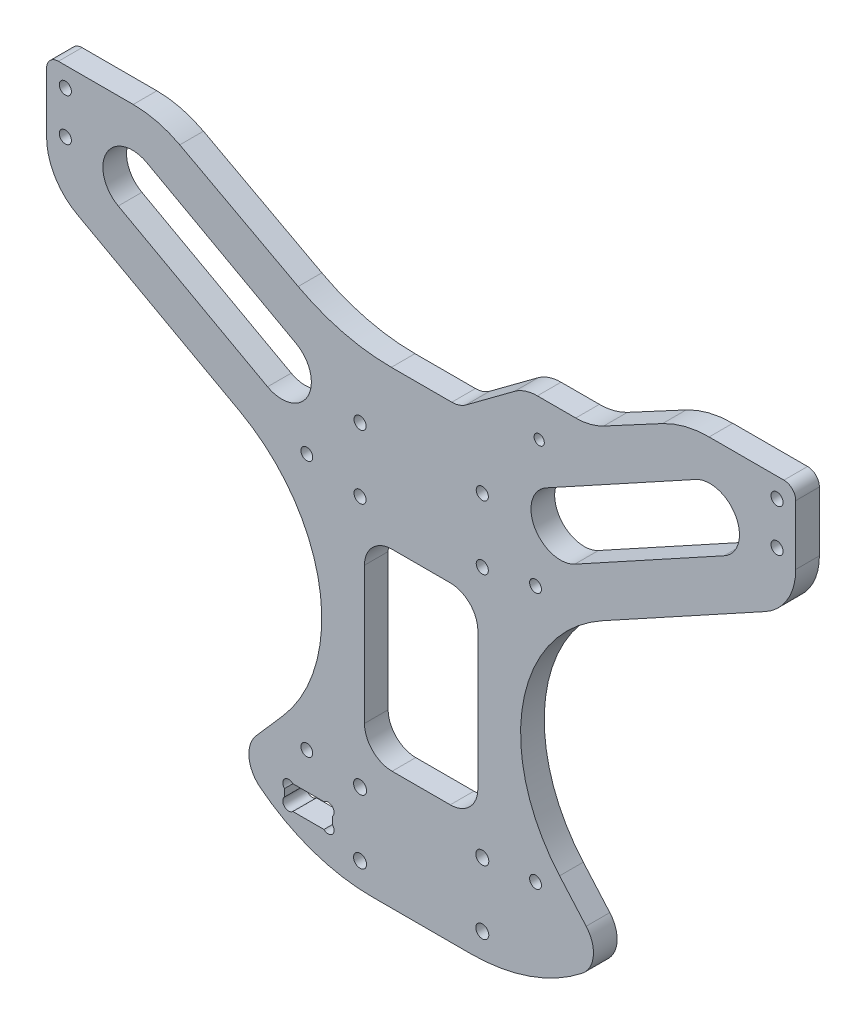
SolidWorks part; units mm, degrees
ref_plane "Front Plane" through (0, 0, 0) normal (0, 0, 1) x (1, 0, 0)
ref_plane "Top Plane" through (0, 0, 0) normal (0, 1, 0) x (1, 0, 0)
ref_plane "Right Plane" through (0, 0, 0) normal (1, 0, 0) x (0, 0, -1)
ref_plane "Plane1" through (0, 0, 0) normal (0, 0, -1) x (-1, 0, 0)
sketch "Sketch1" plane through (0, 0, 0) normal (0, 0, -1) x (-1, 0, 0)
  line L0 (190, 233.5) -> (190, 287.5)
  line L1 (190, 287.5) -> (-190, 287.5)
  line L2 (-190, 287.5) -> (-190, 233.5)
  line L3 (-190, 233.5) -> (-91.9961, 179.7332)
  line L4 (-70.2149, 56.792) -> (-93.1615, 30.5402)
  line L5 (-25, 0) -> (25, 0)
  line L6 (93.1615, 30.5402) -> (70.2149, 56.792)
  line L7 (91.9961, 179.7332) -> (190, 233.5)
  arc A0 (-91.9961, 179.7332) -> (-70.2149, 56.792) centre (-130.5233, 109.5074) cw
  arc A1 (-93.1615, 30.5402) -> (-25, 0) centre (-25, 91.3336) ccw
  arc A2 (25, 0) -> (93.1615, 30.5402) centre (25, 91.3336) ccw
  arc A3 (70.2149, 56.792) -> (91.9961, 179.7332) centre (130.5233, 109.5074) cw
  circle A4 centre (-59.8577, 243.186) radius 2.6
extrude "Boss-Extrude1" add sketch "Sketch1" against normal blind 12
sketch "Sketch2" plane through (0, 0, 12) normal (0, 0, 1) x (1, 0, 0)
  line L0 (133.5, 287.5) -> (-133.5, 287.5)
  line L1 (-133.5, 287.5) -> (-40.2504, 237.5)
  line L2 (-40.2504, 237.5) -> (19.5, 237.5)
  line L3 (19.5, 237.5) -> (52.5, 262)
  line L4 (52.5, 262) -> (85.9427, 262)
  line L5 (85.9427, 262) -> (133.5, 287.5)
extrude "Cut-Extrude1" cut sketch "Sketch2" against normal through all
sketch "Sketch3" plane through (0, 0, 0) normal (0, 0, -1) x (-1, 0, 0)
  line L0 (28.75, 60.25) -> (28.75, 157.75)
  line L1 (28.75, 157.75) -> (-28.75, 157.75)
  line L2 (-28.75, 157.75) -> (-28.75, 60.25)
  line L3 (-28.75, 60.25) -> (28.75, 60.25)
extrude "Cut-Extrude2" cut sketch "Sketch3" against normal through all
sketch "Sketch4" plane through (0, 0, 0) normal (0, 0, -1) x (-1, 0, 0)
  line L0 (-153.664, 239.1065) -> (-77.9148, 197.5491)
  line L1 (-63.4852, 223.8509) -> (-139.2344, 265.4083)
  arc A0 (-77.9148, 197.5491) -> (-63.4852, 223.8509) centre (-70.7, 210.7) ccw
  arc A1 (-139.2344, 265.4083) -> (-153.664, 239.1065) centre (-146.4492, 252.2574) ccw
extrude "Cut-Extrude3" cut sketch "Sketch4" against normal through all
sketch "Sketch5" plane through (0, 0, 12) normal (0, 0, 1) x (1, 0, 0)
  line L0 (-63.4852, 223.8509) -> (-139.2344, 265.4083)
  line L1 (-153.664, 239.1065) -> (-77.9148, 197.5491)
  arc A0 (-77.9148, 197.5491) -> (-63.4852, 223.8509) centre (-70.7, 210.7) ccw
  arc A1 (-139.2344, 265.4083) -> (-153.664, 239.1065) centre (-146.4492, 252.2574) ccw
extrude "Cut-Extrude4" cut sketch "Sketch5" against normal through all
sketch "Sketch6" plane through (0, 0, 12) normal (0, 0, 1) x (1, 0, 0)
  line L0 (-65.0824, 17.4) -> (-49.3176, 17.4)
  line L1 (-69.325, 25.3574) -> (-69.325, 21.6426)
  line L2 (-49.3176, 29.6) -> (-65.0824, 29.6)
  line L3 (-45.075, 25.3574) -> (-45.075, 21.6426)
  arc A0 (-49.3176, 17.4) -> (-45.075, 21.6426) centre (-47.1963, 19.5213) ccw
  arc A1 (-45.075, 25.3574) -> (-49.3176, 29.6) centre (-47.1963, 27.4787) ccw
  arc A2 (-65.0824, 29.6) -> (-69.325, 25.3574) centre (-67.2037, 27.4787) ccw
  arc A3 (-69.325, 21.6426) -> (-65.0824, 17.4) centre (-67.2037, 19.5213) ccw
  dimension "D1" = 12.2
extrude "Cut-Extrude5" cut sketch "Sketch6" against normal through all
sketch "Sketch7" plane through (0, 0, 0) normal (0, 0, -1) x (-1, 0, 0)
  line L0 (26, 39.45) -> (36, 39.45)
  line L1 (36, 39.45) -> (36, 50.95)
  line L2 (36, 50.95) -> (26, 50.95)
  line L3 (26, 50.95) -> (26, 39.45)
extrude "Cut-Extrude6" cut sketch "Sketch7" against normal blind 7
sketch "Sketch8" plane through (0, 0, 0) normal (0, 0, -1) x (-1, 0, 0)
  line L0 (-36, 50.95) -> (-36, 39.45)
  line L1 (-36, 39.45) -> (-26, 39.45)
  line L2 (-26, 39.45) -> (-26, 50.95)
  line L3 (-26, 50.95) -> (-36, 50.95)
extrude "Cut-Extrude7" cut sketch "Sketch8" against normal blind 7
sketch "Sketch9" plane through (0, 0, 0) normal (0, 0, -1) x (-1, 0, 0)
  line L0 (-36, 7.05) -> (-26, 7.05)
  line L1 (-26, 7.05) -> (-26, 18.55)
  line L2 (-26, 18.55) -> (-36, 18.55)
  line L3 (-36, 18.55) -> (-36, 7.05)
extrude "Cut-Extrude8" cut sketch "Sketch9" against normal blind 7
sketch "Sketch10" plane through (0, 0, 0) normal (0, 0, -1) x (-1, 0, 0)
  line L0 (26, 7.05) -> (36, 7.05)
  line L1 (36, 7.05) -> (36, 18.55)
  line L2 (36, 18.55) -> (26, 18.55)
  line L3 (26, 18.55) -> (26, 7.05)
extrude "Cut-Extrude9" cut sketch "Sketch10" against normal blind 7
sketch "Sketch11" plane through (0, 0, 0) normal (0, 0, -1) x (-1, 0, 0)
  line L0 (-26, 178.55) -> (-36, 178.55)
  line L1 (-36, 178.55) -> (-36, 167.05)
  line L2 (-36, 167.05) -> (-26, 167.05)
  line L3 (-26, 167.05) -> (-26, 178.55)
extrude "Cut-Extrude10" cut sketch "Sketch11" against normal blind 7
sketch "Sketch12" plane through (0, 0, 0) normal (0, 0, -1) x (-1, 0, 0)
  line L0 (26, 210.95) -> (26, 199.45)
  line L1 (26, 199.45) -> (36, 199.45)
  line L2 (36, 199.45) -> (36, 210.95)
  line L3 (36, 210.95) -> (26, 210.95)
extrude "Cut-Extrude11" cut sketch "Sketch12" against normal blind 7
sketch "Sketch13" plane through (0, 0, 0) normal (0, 0, -1) x (-1, 0, 0)
  line L0 (26, 167.05) -> (36, 167.05)
  line L1 (36, 167.05) -> (36, 178.55)
  line L2 (36, 178.55) -> (26, 178.55)
  line L3 (26, 178.55) -> (26, 167.05)
extrude "Cut-Extrude12" cut sketch "Sketch13" against normal blind 7
sketch "Sketch14" plane through (0, 0, 0) normal (0, 0, -1) x (-1, 0, 0)
  line L0 (-26, 210.95) -> (-36, 210.95)
  line L1 (-36, 210.95) -> (-36, 199.45)
  line L2 (-36, 199.45) -> (-26, 199.45)
  line L3 (-26, 199.45) -> (-26, 210.95)
extrude "Cut-Extrude13" cut sketch "Sketch14" against normal blind 7
sketch "Sketch15" plane through (0, 0, 0) normal (0, 0, -1) x (-1, 0, 0)
  line L0 (-175.5, 261.75) -> (-185.5, 261.75)
  line L1 (-185.5, 261.75) -> (-185.5, 250.25)
  line L2 (-185.5, 250.25) -> (-175.5, 250.25)
  line L3 (-175.5, 250.25) -> (-175.5, 261.75)
extrude "Cut-Extrude14" cut sketch "Sketch15" against normal blind 7
sketch "Sketch16" plane through (0, 0, 0) normal (0, 0, -1) x (-1, 0, 0)
  line L0 (175.5, 271.75) -> (185.5, 271.75)
  line L1 (185.5, 271.75) -> (185.5, 283.25)
  line L2 (185.5, 283.25) -> (175.5, 283.25)
  line L3 (175.5, 283.25) -> (175.5, 271.75)
extrude "Cut-Extrude15" cut sketch "Sketch16" against normal blind 7
sketch "Sketch17" plane through (0, 0, 0) normal (0, 0, -1) x (-1, 0, 0)
  line L0 (175.5, 261.75) -> (175.5, 250.25)
  line L1 (175.5, 250.25) -> (185.5, 250.25)
  line L2 (185.5, 250.25) -> (185.5, 261.75)
  line L3 (185.5, 261.75) -> (175.5, 261.75)
extrude "Cut-Extrude16" cut sketch "Sketch17" against normal blind 7
sketch "Sketch18" plane through (0, 0, 0) normal (0, 0, -1) x (-1, 0, 0)
  line L0 (-175.5, 283.25) -> (-185.5, 283.25)
  line L1 (-185.5, 283.25) -> (-185.5, 271.75)
  line L2 (-185.5, 271.75) -> (-175.5, 271.75)
  line L3 (-175.5, 271.75) -> (-175.5, 283.25)
extrude "Cut-Extrude17" cut sketch "Sketch18" against normal blind 7
hole_wizard "#12 Clearance Hole1" positions "Sketch20" profile "Sketch19" hole size "#12" standard "ANSI Inch"
sketch "Sketch20" plane through (0, 0, 12) normal (0, 0, 1) x (1, 0, 0)
  point P0 (58, 48)
  point P1 (-58, 178)
  point P2 (58, 178)
  point P3 (-58, 48)
sketch "Sketch19" plane through (58, 48, 12) normal (1, 0, 0) x (0, -1, 0)
  line L0 (0, 0) -> (0, 12)
  line L1 (0, 12) -> (3, 12)
  line L2 (3, 12) -> (3, 0)
  line L5 (3, 0) -> (0, 0)
  line L11 (0, -6.35) -> (0, 107.95) construction
  dimension "Thru Hole Dia." = 6
  dimension "Thru Hole Depth" = 12
hole_wizard "#12 Clearance Hole2" positions "Sketch22" profile "Sketch21" hole size "#12" standard "ANSI Inch"
sketch "Sketch22" plane through (0, 0, 12) normal (0, 0, 1) x (1, 0, 0)
  point P0 (31, 172.8)
  point P1 (-31, 205.2)
  point P2 (-31, 172.8)
  point P3 (31, 205.2)
  point P4 (180.5, 256)
  point P5 (-180.5, 277.5)
  point P6 (-180.5, 256)
  point P7 (180.5, 277.5)
sketch "Sketch21" plane through (31, 172.8, 12) normal (1, 0, 0) x (0, -1, 0)
  line L0 (0, 0) -> (0, 12)
  line L1 (0, 12) -> (3.075, 12)
  line L2 (3.075, 12) -> (3.075, 0)
  line L5 (3.075, 0) -> (0, 0)
  line L11 (0, -6.35) -> (0, 107.95) construction
  dimension "Thru Hole Dia." = 6.15
  dimension "Thru Hole Depth" = 12
hole_wizard "1/4 Clearance Hole1" positions "Sketch24" profile "Sketch23" hole size "1/4" standard "ANSI Inch"
sketch "Sketch24" plane through (0, 0, 12) normal (0, 0, 1) x (1, 0, 0)
  point P0 (-31, 45.2)
  point P1 (31, 45.2)
  point P2 (31, 12.8)
  point P3 (-31, 12.8)
sketch "Sketch23" plane through (-31, 45.2, 12) normal (1, 0, 0) x (0, -1, 0)
  line L0 (0, 0) -> (0, 12)
  line L1 (0, 12) -> (3.3, 12)
  line L2 (3.3, 12) -> (3.3, 0)
  line L5 (3.3, 0) -> (0, 0)
  line L11 (0, -6.35) -> (0, 107.95) construction
  dimension "Thru Hole Dia." = 6.6
  dimension "Thru Hole Depth" = 12
fillet "Fillet1" radius 3 48 edges at (-26, 210.95, 3.5) (36, 210.95, 3.5) (36, 50.95, 3.5) (-185.5, 283.25, 3.5) (-175.5, 250.25, 3.5) (-175.5, 283.25, 3.5) (36, 18.55, 3.5) (-175.5, 271.75, 3.5) (26, 199.45, 3.5) (185.5, 250.25, 3.5) (-185.5, 261.75, 3.5) (175.5, 250.25, 3.5) (36, 167.05, 3.5) (175.5, 261.75, 3.5) (-26, 199.45, 3.5) (185.5, 261.75, 3.5) (26, 7.05, 3.5) (-36, 178.55, 3.5) (26, 178.55, 3.5) (-26, 178.55, 3.5) (26, 210.95, 3.5) (-26, 167.05, 3.5) (-185.5, 250.25, 3.5) (-36, 167.05, 3.5) (-175.5, 261.75, 3.5) (175.5, 271.75, 3.5) (185.5, 283.25, 3.5) (175.5, 283.25, 3.5) (-36, 210.95, 3.5) (-26, 7.05, 3.5) (26, 167.05, 3.5) (-36, 7.05, 3.5) (-36, 199.45, 3.5) (-36, 50.95, 3.5) (36, 7.05, 3.5) (-26, 50.95, 3.5) (26, 18.55, 3.5) (36, 39.45, 3.5) (-185.5, 271.75, 3.5) (26, 39.45, 3.5) (-26, 39.45, 3.5) (26, 50.95, 3.5) (-36, 39.45, 3.5) (36, 178.55, 3.5) (36, 199.45, 3.5) (-36, 18.55, 3.5) (185.5, 271.75, 3.5) (-26, 18.55, 3.5)
fillet "Fillet2" radius 6 2 edges at (-190, 287.5, 6) (190, 287.5, 6)
fillet "Fillet3" radius 12 1 edges at (19.5, 237.5, 6)
fillet "Fillet4" radius 14 4 edges at (-28.75, 157.75, 6) (-28.75, 60.25, 6) (28.75, 60.25, 6) (28.75, 157.75, 6)
fillet "Fillet5" radius 15 2 edges at (93.1615, 30.5402, 6) (-93.1615, 30.5402, 6)
fillet "Fillet6" radius 19.5 1 edges at (52.5, 262, 6)
fillet "Fillet7" radius 30 3 edges at (85.9427, 262, 6) (-190, 233.5, 6) (190, 233.5, 6)
fillet "Fillet8" radius 50 2 edges at (133.5, 287.5, 6) (-133.5, 287.5, 6)
fillet "Fillet9" radius 100 1 edges at (-40.2504, 237.5, 6)
sketch "Sketch25" plane through (0, 0, 0) normal (0, 0, -1) x (-1, 0, 0)
  line L1 (-60.9577, 238.186) -> (-58.7577, 238.186)
  line L2 (-63.9577, 241.186) -> (-63.9577, 245.186)
  line L3 (-60.9577, 248.186) -> (-58.7577, 248.186)
  line L4 (-55.7577, 241.186) -> (-55.7577, 245.186)
  line L5 (-63.9577, 238.186) -> (-55.7577, 248.186) construction
  line L6 (-63.9577, 248.186) -> (-55.7577, 238.186) construction
  arc A0 (-58.7577, 248.186) -> (-55.7577, 245.186) centre (-58.7577, 245.186) cw
  arc A1 (-58.7577, 238.186) -> (-55.7577, 241.186) centre (-58.7577, 241.186) ccw
  arc A2 (-60.9577, 238.186) -> (-63.9577, 241.186) centre (-60.9577, 241.186) cw
  arc A3 (-63.9577, 245.186) -> (-60.9577, 248.186) centre (-60.9577, 245.186) cw
  point P0 (-59.8577, 243.186)
  dimension "D3" = 3
  dimension "D1" = 8.2
  dimension "D2" = 10
extrude "Cut-Extrude18" cut sketch "Sketch25" against normal blind 5
